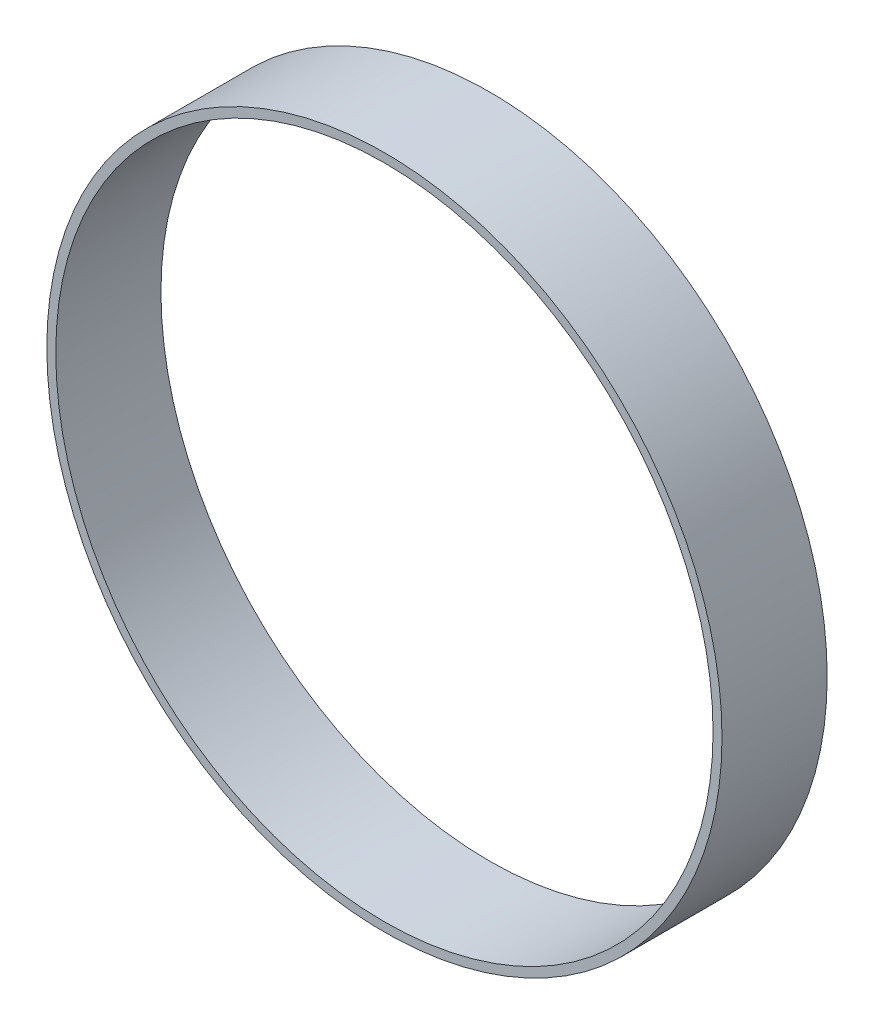
SolidWorks part; units mm, degrees
ref_plane "Front Plane" through (0, 0, 0) normal (0, 0, 1) x (1, 0, 0)
ref_plane "Top Plane" through (0, 0, 0) normal (0, 1, 0) x (1, 0, 0)
ref_plane "Right Plane" through (0, 0, 0) normal (1, 0, 0) x (0, 0, -1)
sketch "Sketch1" plane through (0, 0, 0) normal (0, 0, 1) x (1, 0, 0)
  circle A0 centre (0, 0) radius 62.5
  circle A1 centre (0, 0) radius 64.2
  dimension "D1" = 125
  dimension "D2" = 128.4
extrude "Boss-Extrude1" add sketch "Sketch1" along normal blind 20
